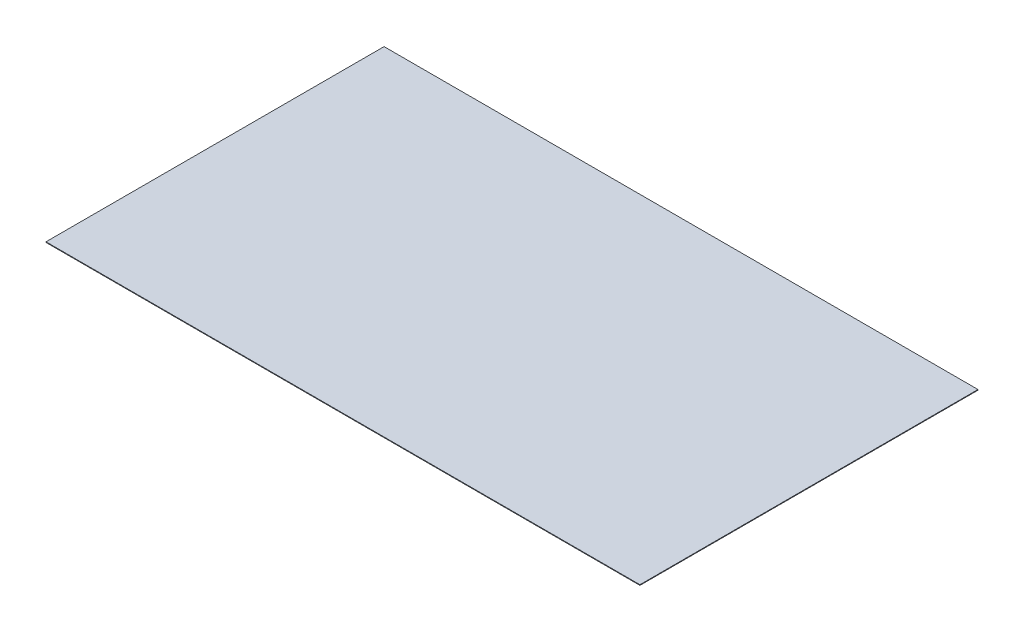
SolidWorks part; units mm, degrees
ref_plane "Alzado" through (0, 0, 0) normal (0, 0, 1) x (1, 0, 0)
ref_plane "Planta" through (0, 0, 0) normal (0, 1, 0) x (1, 0, 0)
ref_plane "Vista lateral" through (0, 0, 0) normal (1, 0, 0) x (0, 0, -1)
sketch "Croquis1" plane through (0, 0, 0) normal (0, 1, 0) x (1, 0, 0)
  line L1 (969.75, -552) -> (-969.75, -552)
  line L2 (969.75, -552) -> (969.75, 552)
  line L3 (969.75, 552) -> (-969.75, 552)
  line L4 (-969.75, -552) -> (-969.75, 552)
  line L5 (969.75, -552) -> (-969.75, 552) construction
  line L6 (969.75, 552) -> (-969.75, -552) construction
  point P0 (0, 0)
  dimension "D1" = 1939.5
  dimension "D2" = 1104
extrude "Extruir1" add sketch "Croquis1" along normal blind 2
